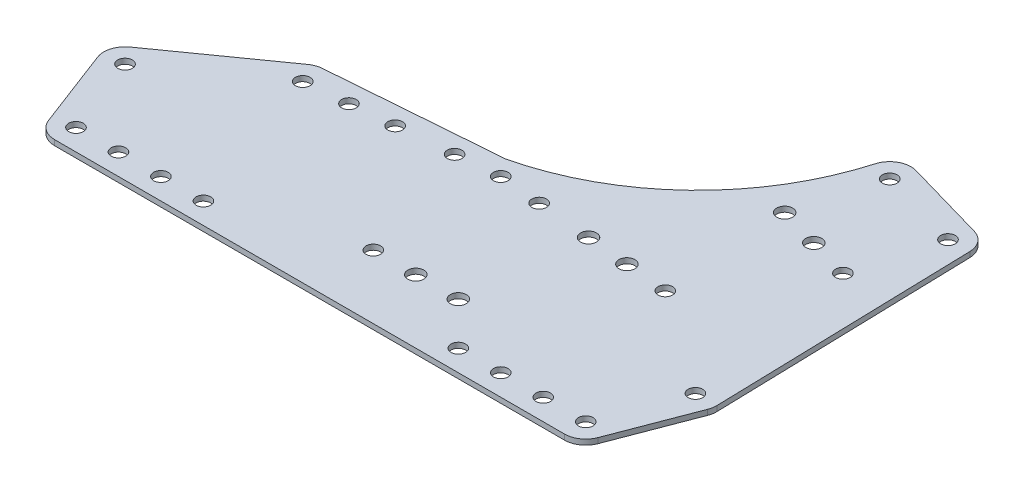
SolidWorks part; units mm, degrees
ref_plane "Front Plane" through (0, 0, 0) normal (0, 0, 1) x (1, 0, 0)
ref_plane "Top Plane" through (0, 0, 0) normal (0, 1, 0) x (1, 0, 0)
ref_plane "Right Plane" through (0, 0, 0) normal (1, 0, 0) x (0, 0, -1)
sketch "Sketch1" plane through (0, 0, 0) normal (0, 1, 0) x (1, 0, 0)
  line L1 (-76.2, -19.05) -> (76.2, -19.05)
  line L2 (-91.1942, 8.7629) -> (-82.1321, -14.9655)
  line L3 (-88.9388, 16.2058) -> (-57.8746, 38.2655)
  line L4 (-54.6898, 39.4191) -> (-3.711, 43.3788)
  line L5 (91.1942, 8.7629) -> (82.1321, -14.9655)
  line L11 (60.5259, 101.7104) -> (84.9437, 94.7154)
  line L14 (89.5427, 88.7801) -> (91.6099, 11.1976)
  circle A0 centre (0, 0) radius 2.1828
  circle A1 centre (12.7, 0) radius 2.3813
  circle A2 centre (25.4, 0) radius 2.3813
  circle A3 centre (-38.1, -12.7) radius 2.1828
  circle A4 centre (-50.8, -12.7) radius 2.1828
  circle A5 centre (-63.5, -12.7) radius 2.1828
  circle A6 centre (-76.2, -12.7) radius 2.1828
  circle A7 centre (38.1, -12.7) radius 2.1828
  circle A8 centre (50.8, -12.7) radius 2.1828
  circle A9 centre (63.5, -12.7) radius 2.1828
  circle A10 centre (76.2, -12.7) radius 2.1828
  circle A11 centre (-54.198, 33.0881) radius 2.1828
  circle A12 centre (54.198, 33.0881) radius 2.1828
  circle A13 centre (-85.2621, 11.0284) radius 2.1828
  circle A14 centre (85.2621, 11.0284) radius 2.1828
  circle A15 centre (0, 38.1) radius 2.1828
  circle A16 centre (12.646, 36.9306) radius 2.1828
  circle A17 centre (-12.646, 36.9306) radius 2.1828
  circle A18 centre (41.552, 34.2576) radius 2.3812
  circle A19 centre (28.9059, 35.427) radius 2.3812
  circle A20 centre (76.2, 64.1932) radius 2.1828
  circle A21 centre (51.7822, 71.1881) radius 2.3812
  circle A22 centre (63.9911, 67.6906) radius 2.3813
  arc A23 (-82.1321, -14.9655) -> (-76.2, -19.05) centre (-76.2, -12.7) ccw
  arc A24 (-91.1942, 8.7629) -> (-88.9388, 16.2058) centre (-85.2621, 11.0284) cw
  arc A25 (-57.8746, 38.2655) -> (-54.6898, 39.4191) centre (-54.198, 33.0881) cw
  arc A26 (76.2, -19.05) -> (82.1321, -14.9655) centre (76.2, -12.7) ccw
  circle A31 centre (-41.552, 34.2576) radius 2.1828
  circle A32 centre (-28.9059, 35.427) radius 2.1828
  circle A33 centre (58.7771, 95.606) radius 2.1828
  circle A34 centre (83.195, 88.611) radius 2.1828
  arc A35 (84.9437, 94.7154) -> (89.5427, 88.7801) centre (83.195, 88.611) cw
  arc A36 (91.1942, 8.7629) -> (91.6099, 11.1976) centre (85.2621, 11.0284) ccw
  arc A37 (52.6727, 97.3547) -> (60.5259, 101.7104) centre (58.7771, 95.606) cw
  arc A38 (52.6727, 97.3547) -> (-3.711, 43.3788) centre (-21.7694, 118.6801) cw
  point P73 (-2.0019, 43.937)
  dimension "D3" = 4.3656
  dimension "D4" = 4.7625
  dimension "D5" = 4.7625
  dimension "D8" = 4.3656
  dimension "D15" = 4.3656
  dimension "D16" = 4.3656
  dimension "D19" = 4.3656
  dimension "D22" = 4.3656
  dimension "D25" = 4.3656
  dimension "D28" = 4.3656
  dimension "D31" = 4.3656
  dimension "D33" = 4.3656
  dimension "D37" = 4.3656
  dimension "D40" = 4.3656
  dimension "D43" = 4.3656
  dimension "D46" = 4.3656
  dimension "D49" = 4.3656
  dimension "D50" = 4.3656
  dimension "D53" = 4.7625
  dimension "D54" = 4.7625
  dimension "D61" = 4.3656
  dimension "D63" = 4.7625
  dimension "D64" = 4.7625
  dimension "D75" = 4.3656
  dimension "D76" = 4.3656
  dimension "D83" = 4.3656
  dimension "D85" = 4.3656
  dimension "D1" = 12.7
  dimension "D2" = 12.7
  dimension "D6" = 0
  dimension "D7" = 0
  dimension "D9" = 12.7
  dimension "D10" = 38.1
  dimension "D11" = 0
  dimension "D12" = 12.7
  dimension "D13" = 0
  dimension "D14" = 12.7
  dimension "D17" = 0
  dimension "D18" = 12.7
  dimension "D20" = 12.7
  dimension "D21" = 12.7
  dimension "D23" = 12.7
  dimension "D24" = 0
  dimension "D26" = 0
  dimension "D27" = 12.7
  dimension "D29" = 0
  dimension "D30" = 12.7
  dimension "D32" = 50.8
  dimension "D34" = 63.5
  dimension "D35" = 63.5
  dimension "D36" = 50.8
  dimension "D38" = 25.4
  dimension "D39" = 38.1
  dimension "D41" = 25.4
  dimension "D42" = 38.1
  dimension "D44" = 0
  dimension "D45" = 38.1
  dimension "D47" = 12.7
  dimension "D48" = 12.7
  dimension "D51" = 12.7
  dimension "D52" = 12.7
  dimension "D55" = 12.646
  dimension "D56" = 12.646
  dimension "D57" = 28.9059
  dimension "D58" = 35.427
  dimension "D59" = 38.1
  dimension "D60" = 0
  dimension "D62" = 25.4
  dimension "D65" = 38.1
  dimension "D66" = 63.9911
  dimension "D67" = 67.6906
  dimension "D68" = 25.4
  dimension "D69" = 6.35
  dimension "D70" = 6.35
  dimension "D71" = 6.35
  dimension "D72" = 6.35
  dimension "D73" = 6.35
  dimension "D74" = 12.7
  dimension "D77" = 83.195
  dimension "D78" = 6.35
  dimension "D79" = 58.7771
  dimension "D80" = 25.4
  dimension "D81" = 6.35
  dimension "D82" = 25.4
  dimension "D87" = 6.35
  dimension "D88" = 6.35
  dimension "D89" = 6.35
extrude "Boss-Extrude1" add sketch "Sketch1" along normal blind 1.5875
